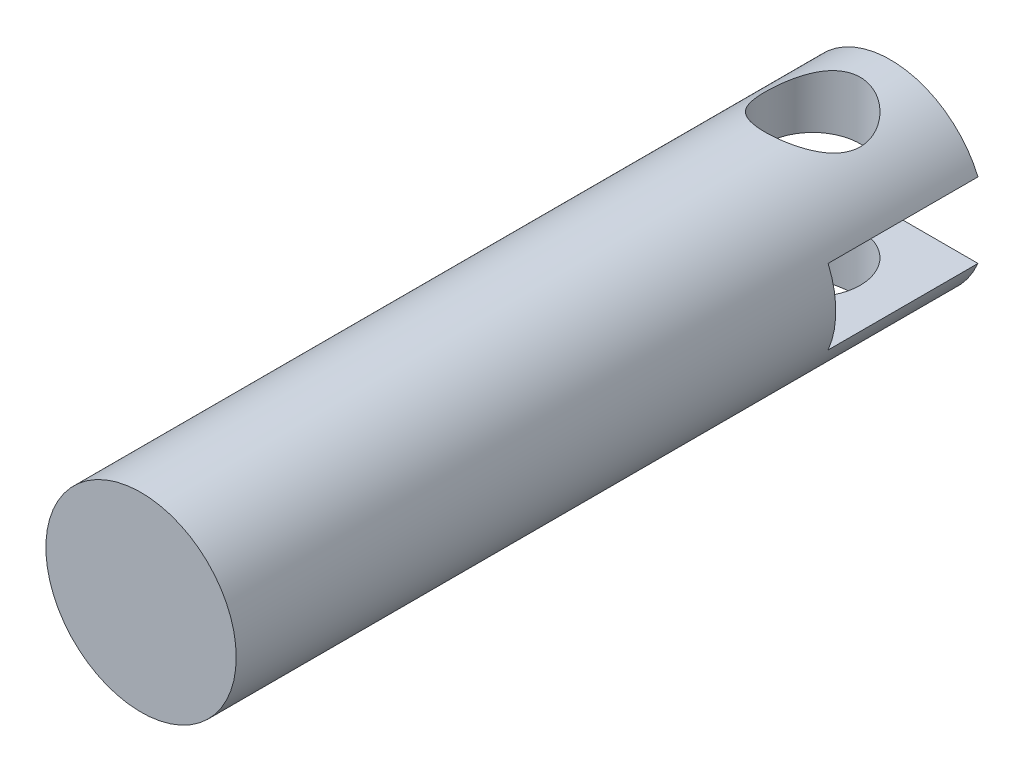
SolidWorks part; units mm, degrees
ref_plane "Alzado" through (0, 0, 0) normal (0, 0, 1) x (1, 0, 0)
ref_plane "Planta" through (0, 0, 0) normal (0, 1, 0) x (1, 0, 0)
ref_plane "Vista lateral" through (0, 0, 0) normal (1, 0, 0) x (0, 0, -1)
sketch "Croquis1" plane through (0, 0, 0) normal (0, 0, 1) x (1, 0, 0)
  circle A0 centre (0, 0) radius 6.35
  dimension "D1" = 12.7
extrude "Saliente-Extruir1" add sketch "Croquis1" along normal blind 50
sketch "Croquis2" plane through (0, 0, 0) normal (0, 0, -1) x (-1, 0, 0)
  line L1 (-10.8822, -2.5) -> (10.8822, -2.5)
  line L2 (-10.8822, -2.5) -> (-10.8822, 2.5)
  line L3 (-10.8822, 2.5) -> (10.8822, 2.5)
  line L4 (10.8822, -2.5) -> (10.8822, 2.5)
  line L5 (-10.8822, -2.5) -> (10.8822, 2.5) construction
  line L6 (-10.8822, 2.5) -> (10.8822, -2.5) construction
  point P0 (0, 0)
  dimension "D1" = 5
extrude "Cortar-Extruir1" cut sketch "Croquis2" against normal blind 10
sketch "Croquis3" plane through (0, 0, 0) normal (0, 1, 0) x (1, 0, 0)
  circle A0 centre (0, -5.1914) radius 3.175
  dimension "D1" = 6.35
extrude "Cortar-Extruir2" cut sketch "Croquis3" along normal through all and the other way blind 15.5262
